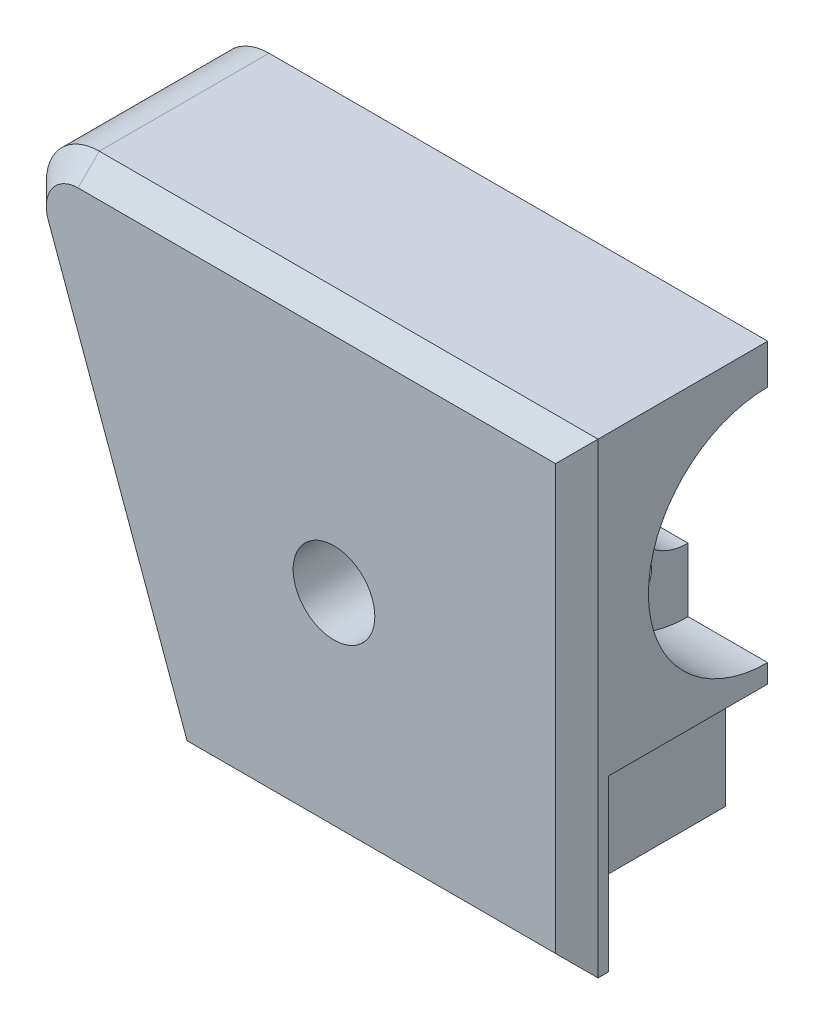
SolidWorks part; units mm, degrees
material "Custom Plastic"
ref_plane "Front Plane" through (0, 0, 0) normal (0, 0, 1) x (1, 0, 0)
ref_plane "Top Plane" through (0, 0, 0) normal (0, 1, 0) x (1, 0, 0)
ref_plane "Right Plane" through (0, 0, 0) normal (1, 0, 0) x (0, 0, -1)
sketch "Sketch1" plane through (0, 0, 0) normal (0, 0, 1) x (1, 0, 0)
  line L0 (0, 0) -> (30, 0)
  line L1 (30, 0) -> (30, -8)
  line L2 (30, -8) -> (2.9118, -8)
  line L3 (2.9118, -8) -> (0, 0)
  dimension "D1" = 70
  dimension "D2" = 8
  dimension "D3" = 30
extrude "Boss-Extrude1" add sketch "Sketch1" along normal blind 15
sketch "Sketch2" plane through (0, 0, 15) normal (0, 0, 1) x (1, 0, 0)
  line L4 (0, 0) -> (2.9118, -8)
  line L5 (2.9118, -8) -> (30, -8)
  line L6 (30, -8) -> (30, 0)
  line L7 (30, 0) -> (0, 0)
  line L8 (0, 0) -> (2.9118, -8) construction
  line L9 (2.9118, -8) -> (30, -8) construction
  line L10 (30, -8) -> (30, 0) construction
  line L11 (30, 0) -> (0, 0) construction
  line L16 (-11.4252, 8) -> (-2.6899, -16)
  line L17 (-2.6899, -16) -> (38, -16)
  line L18 (38, -16) -> (38, 8)
  line L19 (38, 8) -> (-11.4252, 8)
  line L20 (-11.4252, 8) -> (-2.6899, -16)
  line L21 (-2.6899, -16) -> (38, -16)
  line L22 (38, -16) -> (38, 8)
  line L23 (38, 8) -> (-11.4252, 8)
  dimension "D1" = 0
  dimension "D2" = 8
extrude "Boss-Extrude2" add sketch "Sketch2" along normal blind 3
sketch "Sketch3" plane through (0, 0, 0) normal (0, 0, -1) x (-1, 0, 0)
  line L0 (5.7126, 4) -> (-34, 4)
  line L1 (-34, 4) -> (-34, -12)
  line L3 (-0.1109, -12) -> (5.7126, 4)
  line L4 (-2.9118, -8) -> (0, 0)
  line L5 (0, 0) -> (-30, 0)
  line L6 (-30, 0) -> (-30, -8)
  line L7 (-30, -8) -> (-2.9118, -8)
  line L8 (-2.9118, -8) -> (0, 0) construction
  line L9 (0, 0) -> (-30, 0) construction
  line L10 (-30, 0) -> (-30, -8) construction
  line L11 (-30, -8) -> (-2.9118, -8) construction
  line L12 (-38, 8) -> (-38, -16)
  line L14 (2.6899, -16) -> (11.4252, 8)
  line L15 (11.4252, 8) -> (-38, 8)
  line L16 (-34, -12) -> (-34, -16)
  line L17 (2.6899, -16) -> (-38, -16) construction
  line L18 (-34, -16) -> (-38, -16)
  line L19 (-0.1109, -12) -> (-1.5668, -16)
  line L20 (-34, -12) -> (-0.1109, -12) construction
  line L21 (-1.5668, -16) -> (2.6899, -16)
  dimension "D1" = 0
  dimension "D2" = 4
extrude "Boss-Extrude3" add sketch "Sketch3" against normal up to surface (15 mm away) up to face at (15.7279, -4, 15)
sketch "Sketch4" plane through (0, 0, 0) normal (0, 0, -1) x (-1, 0, 0)
  line L0 (-1.5668, -16) -> (-34, -16) construction
  line L1 (-38, 8) -> (-34, 8)
  line L2 (-38, 8) -> (-38, -16)
  line L3 (-38, -16) -> (-30, -16)
  line L4 (-34, 8) -> (-34, -12)
  line L6 (2.6899, -16) -> (11.4252, 8) construction
  line L7 (-30, -16) -> (4.1458, -16)
  line L9 (-34, -12) -> (4.1458, -12)
  line L10 (4.1458, -16) -> (4.1458, -12)
  line L11 (-34, -16) -> (-34, 4) construction
  dimension "D1" = 4
extrude "Cut-Extrude1" cut sketch "Sketch4" against normal through all
fillet "Fillet2" radius 2 1 edges at (-5.7126, 4, 7.5)
sketch "Sketch5" plane through (0, 0, 0) normal (0, 0, -1) x (-1, 0, 0)
  line L0 (11.4252, 8) -> (20.1605, 32)
  line L1 (20.1605, 32) -> (-34, 32)
  line L2 (-34, 32) -> (-34, 8)
  line L3 (-34, 8) -> (11.4252, 8)
  line L4 (4.1458, -12) -> (11.4252, 8) construction
  line L5 (-34, 4) -> (-34, 8) construction
  dimension "D1" = 24
extrude "Boss-Extrude4" add sketch "Sketch5" against normal up to surface (18 mm away) up to face at (13.1073, -2, 18)
sketch "Sketch6" plane through (34, 0, 0) normal (1, 0, 0) x (0, 0, -1)
  line L0 (0, 4) -> (0, 32) construction
  line L1 (-18, 32) -> (0, 32) construction
  circle A0 centre (0, 17) radius 5.25 construction
  circle A1 centre (0, 17) radius 11 construction
  dimension "D1" = 10.5
  dimension "D2" = 15
  dimension "D3" = 22
sketch "Sketch7" plane through (0, 0, 0) normal (0, 0, -1) x (-1, 0, 0)
  line L0 (-34, 17) -> (14.7009, 17)
  line L1 (-34, 28) -> (-34, 6) construction
  line L2 (4.1458, -12) -> (20.1605, 32) construction
  line L3 (-34, 17) -> (-34, 28.25)
  line L4 (-34, 28.25) -> (-26.5, 28.25)
  line L5 (-26.5, 28.25) -> (-26.5, 22.25)
  line L6 (-26.5, 22.25) -> (-15, 22.25)
  line L7 (-15, 22.25) -> (-15, 20.25)
  line L8 (-15, 20.25) -> (15.8838, 20.25)
  line L9 (15.8838, 20.25) -> (14.7009, 17)
  dimension "D1" = 11.25
  dimension "D2" = 5.25
  dimension "D3" = 7.5
  dimension "D4" = 11.5
  dimension "D5" = 3.25
revolve "Cut-Revolve1" cut sketch "Sketch7" angle 360 about L0
sketch "Sketch8" plane through (26.5, 0, 0) normal (1, 0, 0) x (0, 0, -1)
  line L0 (0, 17) -> (-5.6569, 22.6569) construction
  line L1 (0, 17) -> (-18, 17) construction
  line L2 (-18, -12) -> (-18, 32) construction
  circle A0 centre (-5.6569, 22.6569) radius 2.2
  circle A1 centre (5.6569, 22.6569) radius 2.2
  circle A2 centre (5.6569, 11.3431) radius 2.2
  circle A3 centre (-5.6569, 11.3431) radius 2.2
  point P16 (0, 17)
  dimension "D3" = 4.4
  dimension "D1" = 45
  dimension "D2" = 8
  dimension "D4" = 4
extrude "Cut-Extrude3" cut sketch "Sketch8" against normal blind 6
fillet "Fillet3" radius 5 1 edges at (-20.1605, 32, 9)
fillet "Fillet4" radius 2 5 edges at (34, 10, 18) (14.9271, -12, 18) (-10.932, 6.6449, 18) (-17.1155, 29.8679, 18) (10.4901, 32, 18) profile chamfer
sketch "Sketch9" plane through (0, 0, 0) normal (0, 0, -1) x (-1, 0, 0)
  line L0 (-34, 9) -> (11.7892, 9) construction
  line L3 (-34, 28) -> (-34, 6) construction
  line L4 (4.1458, -12) -> (13.518, 13.75) construction
  line L5 (2.8563, 4) -> (-34, 4) construction
  circle A0 centre (-11.1054, 9) radius 2.1
  dimension "D1" = 4.2
  dimension "D2" = 5
extrude "Cut-Extrude4" cut sketch "Sketch9" against normal through all and the other way through all
sketch "Sketch10" plane through (0, 0, 18) normal (0, 0, 1) x (1, 0, 0)
  circle A0 centre (11.1054, 9) radius 3.85
  dimension "D1" = 7.7
extrude "Cut-Extrude5" cut sketch "Sketch10" against normal blind 8
